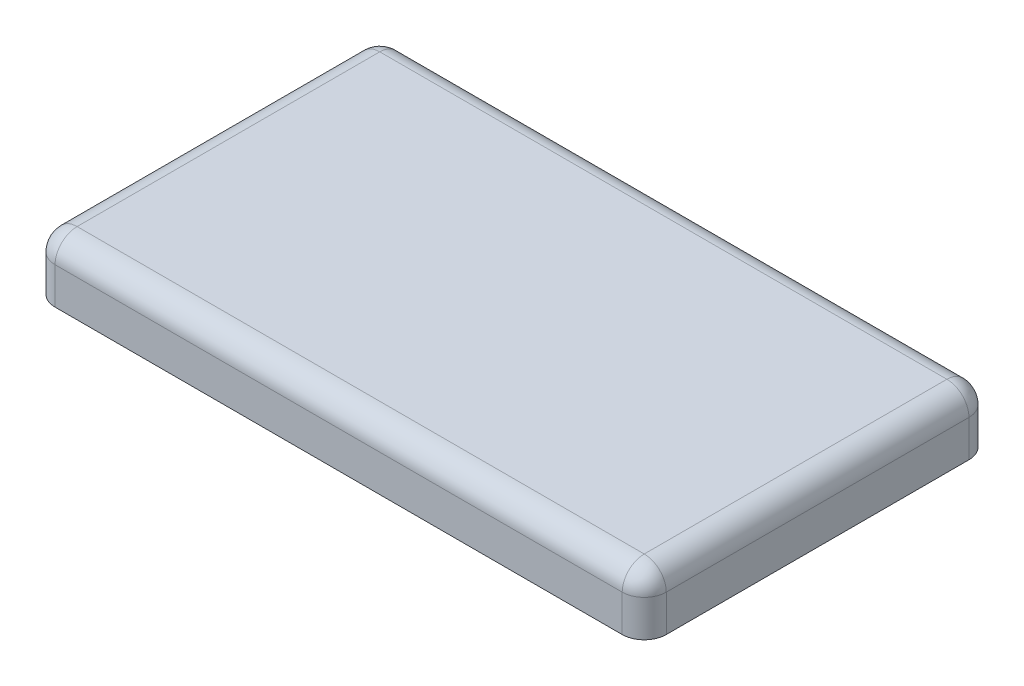
SolidWorks part; units mm, degrees
ref_plane "Front Plane" through (0, 0, 0) normal (0, 0, 1) x (1, 0, 0)
ref_plane "Top Plane" through (0, 0, 0) normal (0, 1, 0) x (1, 0, 0)
ref_plane "Right Plane" through (0, 0, 0) normal (1, 0, 0) x (0, 0, -1)
sketch "Sketch1" plane through (0, 0, 0) normal (0, 1, 0) x (1, 0, 0)
  line L1 (0, 0) -> (41.6, 0)
  line L2 (0, 0) -> (0, 23.6)
  line L3 (0, 23.6) -> (41.6, 23.6)
  line L4 (41.6, 0) -> (41.6, 23.6)
  dimension "D1" = 41.6
  dimension "D2" = 23.6
extrude "Boss-Extrude1" add sketch "Sketch1" along normal blind 4
sketch "Sketch2" plane through (0, 0, 0) normal (0, -1, 0) x (1, 0, 0)
  line L0 (20.8, 0) -> (20.8, -23.6) construction
  line L1 (0, 0) -> (41.6, 0) construction
  line L2 (41.6, -23.6) -> (0, -23.6) construction
  line L4 (1.35, -22.25) -> (40.25, -22.25)
  line L5 (1.35, -22.25) -> (1.35, -1.35)
  line L6 (1.35, -1.35) -> (40.25, -1.35)
  line L7 (40.25, -22.25) -> (40.25, -1.35)
  line L8 (1.35, -22.25) -> (40.25, -1.35) construction
  line L9 (1.35, -1.35) -> (40.25, -22.25) construction
  line L10 (0, -23.6) -> (41.6, -23.6) construction
  line L11 (0, -23.6) -> (0, 0) construction
  line L12 (0, 0) -> (41.6, 0) construction
  line L13 (41.6, -23.6) -> (41.6, 0) construction
  line L14 (0, -23.6) -> (41.6, 0) construction
  line L15 (0, 0) -> (41.6, -23.6) construction
  point P6 (20.8, -11.8)
  point P11 (20.8, -11.8)
  dimension "D1" = 1.35
  dimension "D2" = 1.35
extrude "Cut-Extrude1" cut sketch "Sketch2" against normal blind 2.6
fillet "Fillet1" radius 1.5 8 edges at (20.8, 4, -23.6) (41.6, 4, -11.8) (20.8, 4, 0) (0, 4, -11.8) (0, 2, 0) (0, 2, -23.6) (41.6, 2, -23.6) (41.6, 2, 0)
